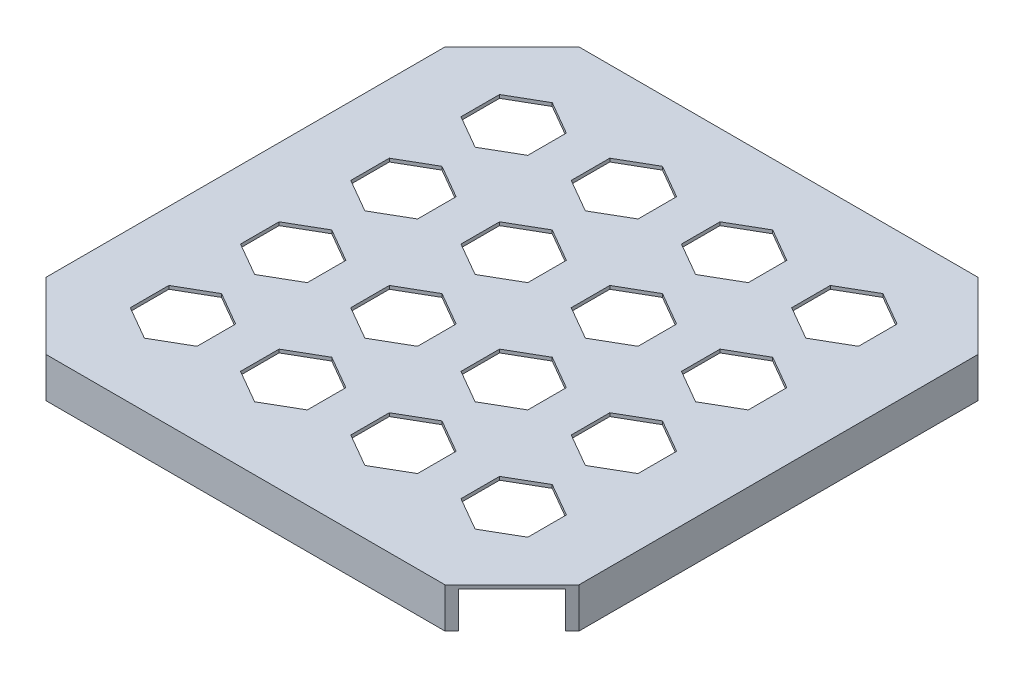
SolidWorks part; units mm, degrees
ref_plane "Front Plane" through (0, 0, 0) normal (0, 0, 1) x (1, 0, 0)
ref_plane "Top Plane" through (0, 0, 0) normal (0, 1, 0) x (1, 0, 0)
ref_plane "Right Plane" through (0, 0, 0) normal (1, 0, 0) x (0, 0, -1)
sketch "Sketch1" plane through (0, 0, 0) normal (0, 1, 0) x (1, 0, 0)
  line L0 (0, 139.5) -> (20, 159.5)
  line L1 (0, 0) -> (159.5, 0)
  line L2 (0, 0) -> (0, 159.5)
  line L3 (0, 159.5) -> (159.5, 159.5)
  line L4 (159.5, 0) -> (159.5, 159.5)
  line L5 (79.75, 159.5) -> (79.75, 0) construction
  line L6 (159.5, 79.75) -> (0, 79.75) construction
  line L7 (159.5, 139.5) -> (139.5, 159.5)
  line L8 (159.5, 20) -> (139.5, 0)
  line L9 (0, 20) -> (20, 0)
  dimension "D1" = 159.5
  dimension "D2" = 159.5
  dimension "D3" = 45
  dimension "D4" = 20
extrude "Boss-Extrude1" add sketch "Sketch1" along normal blind 12 contours L2 L9 L1 L8 L4 L7 L3 L0
sketch "Sketch5" plane through (0, 0, 0) normal (0, -1, 0) x (1, 0, 0)
  line L0 (0, -20) -> (0, -139.5) construction
  line L1 (2, -2) -> (157.5, -2)
  line L2 (2, -2) -> (2, -157.5)
  line L3 (2, -157.5) -> (157.5, -157.5)
  line L4 (157.5, -2) -> (157.5, -157.5)
  line L5 (20, 0) -> (139.5, 0) construction
  dimension "D1" = 2
  dimension "D2" = 2
  dimension "D3" = 155.5
extrude "Cut-Extrude3" cut sketch "Sketch5" against normal blind 11
sketch "Sketch7" plane through (0, 12, 0) normal (0, 1, 0) x (1, 0, 0)
  line L0 (159.5, 20) -> (159.5, 139.5) construction
  line L1 (139.5, 123.7265) -> (139.5, 135.2735)
  line L2 (139.5, 135.2735) -> (129.5, 141.047)
  line L3 (129.5, 141.047) -> (119.5, 135.2735)
  line L4 (119.5, 135.2735) -> (119.5, 123.7265)
  line L5 (119.5, 123.7265) -> (129.5, 117.953)
  line L6 (129.5, 117.953) -> (139.5, 123.7265)
  line L7 (20, 159.5) -> (139.5, 159.5) construction
  line L9 (106.5, 123.7265) -> (106.5, 135.2735)
  line L10 (106.5, 135.2735) -> (96.5, 141.047)
  line L11 (96.5, 141.047) -> (86.5, 135.2735)
  line L12 (86.5, 135.2735) -> (86.5, 123.7265)
  line L13 (86.5, 123.7265) -> (96.5, 117.953)
  line L14 (96.5, 117.953) -> (106.5, 123.7265)
  line L15 (73.5, 123.7265) -> (73.5, 135.2735)
  line L16 (73.5, 135.2735) -> (63.5, 141.047)
  line L17 (63.5, 141.047) -> (53.5, 135.2735)
  line L18 (53.5, 135.2735) -> (53.5, 123.7265)
  line L19 (53.5, 123.7265) -> (63.5, 117.953)
  line L20 (63.5, 117.953) -> (73.5, 123.7265)
  line L21 (40.5, 123.7265) -> (40.5, 135.2735)
  line L22 (40.5, 135.2735) -> (30.5, 141.047)
  line L23 (30.5, 141.047) -> (20.5, 135.2735)
  line L24 (20.5, 135.2735) -> (20.5, 123.7265)
  line L25 (20.5, 123.7265) -> (30.5, 117.953)
  line L26 (30.5, 117.953) -> (40.5, 123.7265)
  line L27 (106.5, 90.7265) -> (106.5, 102.2735)
  line L28 (106.5, 102.2735) -> (96.5, 108.047)
  line L29 (96.5, 108.047) -> (86.5, 102.2735)
  line L30 (86.5, 102.2735) -> (86.5, 90.7265)
  line L31 (86.5, 90.7265) -> (96.5, 84.953)
  line L32 (96.5, 84.953) -> (106.5, 90.7265)
  line L33 (73.5, 90.7265) -> (73.5, 102.2735)
  line L34 (73.5, 102.2735) -> (63.5, 108.047)
  line L35 (63.5, 108.047) -> (53.5, 102.2735)
  line L36 (53.5, 102.2735) -> (53.5, 90.7265)
  line L37 (53.5, 90.7265) -> (63.5, 84.953)
  line L38 (63.5, 84.953) -> (73.5, 90.7265)
  line L39 (40.5, 90.7265) -> (40.5, 102.2735)
  line L40 (40.5, 102.2735) -> (30.5, 108.047)
  line L41 (30.5, 108.047) -> (20.5, 102.2735)
  line L42 (20.5, 102.2735) -> (20.5, 90.7265)
  line L43 (20.5, 90.7265) -> (30.5, 84.953)
  line L44 (30.5, 84.953) -> (40.5, 90.7265)
  line L45 (106.5, 57.7265) -> (106.5, 69.2735)
  line L46 (106.5, 69.2735) -> (96.5, 75.047)
  line L47 (96.5, 75.047) -> (86.5, 69.2735)
  line L48 (86.5, 69.2735) -> (86.5, 57.7265)
  line L49 (86.5, 57.7265) -> (96.5, 51.953)
  line L50 (96.5, 51.953) -> (106.5, 57.7265)
  line L51 (73.5, 57.7265) -> (73.5, 69.2735)
  line L52 (73.5, 69.2735) -> (63.5, 75.047)
  line L53 (63.5, 75.047) -> (53.5, 69.2735)
  line L54 (53.5, 69.2735) -> (53.5, 57.7265)
  line L55 (53.5, 57.7265) -> (63.5, 51.953)
  line L56 (63.5, 51.953) -> (73.5, 57.7265)
  line L57 (40.5, 57.7265) -> (40.5, 69.2735)
  line L58 (40.5, 69.2735) -> (30.5, 75.047)
  line L59 (30.5, 75.047) -> (20.5, 69.2735)
  line L60 (20.5, 69.2735) -> (20.5, 57.7265)
  line L61 (20.5, 57.7265) -> (30.5, 51.953)
  line L62 (30.5, 51.953) -> (40.5, 57.7265)
  line L63 (106.5, 24.7265) -> (106.5, 36.2735)
  line L64 (106.5, 36.2735) -> (96.5, 42.047)
  line L65 (96.5, 42.047) -> (86.5, 36.2735)
  line L66 (86.5, 36.2735) -> (86.5, 24.7265)
  line L67 (86.5, 24.7265) -> (96.5, 18.953)
  line L68 (96.5, 18.953) -> (106.5, 24.7265)
  line L69 (73.5, 24.7265) -> (73.5, 36.2735)
  line L70 (73.5, 36.2735) -> (63.5, 42.047)
  line L71 (63.5, 42.047) -> (53.5, 36.2735)
  line L72 (53.5, 36.2735) -> (53.5, 24.7265)
  line L73 (53.5, 24.7265) -> (63.5, 18.953)
  line L74 (63.5, 18.953) -> (73.5, 24.7265)
  line L75 (40.5, 24.7265) -> (40.5, 36.2735)
  line L76 (40.5, 36.2735) -> (30.5, 42.047)
  line L77 (30.5, 42.047) -> (20.5, 36.2735)
  line L78 (20.5, 36.2735) -> (20.5, 24.7265)
  line L79 (20.5, 24.7265) -> (30.5, 18.953)
  line L80 (30.5, 18.953) -> (40.5, 24.7265)
  line L81 (139.5, 90.7265) -> (139.5, 102.2735)
  line L82 (139.5, 102.2735) -> (129.5, 108.047)
  line L83 (129.5, 108.047) -> (119.5, 102.2735)
  line L84 (119.5, 102.2735) -> (119.5, 90.7265)
  line L85 (119.5, 90.7265) -> (129.5, 84.953)
  line L86 (129.5, 84.953) -> (139.5, 90.7265)
  line L87 (139.5, 57.7265) -> (139.5, 69.2735)
  line L88 (139.5, 69.2735) -> (129.5, 75.047)
  line L89 (129.5, 75.047) -> (119.5, 69.2735)
  line L90 (119.5, 69.2735) -> (119.5, 57.7265)
  line L91 (119.5, 57.7265) -> (129.5, 51.953)
  line L92 (129.5, 51.953) -> (139.5, 57.7265)
  line L93 (139.5, 24.7265) -> (139.5, 36.2735)
  line L94 (139.5, 36.2735) -> (129.5, 42.047)
  line L95 (129.5, 42.047) -> (119.5, 36.2735)
  line L96 (119.5, 36.2735) -> (119.5, 24.7265)
  line L97 (119.5, 24.7265) -> (129.5, 18.953)
  line L98 (129.5, 18.953) -> (139.5, 24.7265)
  circle A0 centre (129.5, 129.5) radius 10 construction
  dimension "D2" = 20
  dimension "D1" = 30
  dimension "D3" = 30
  dimension "D4" = 4
  dimension "D5" = 4
extrude "Cut-Extrude4" cut sketch "Sketch7" against normal blind 11
